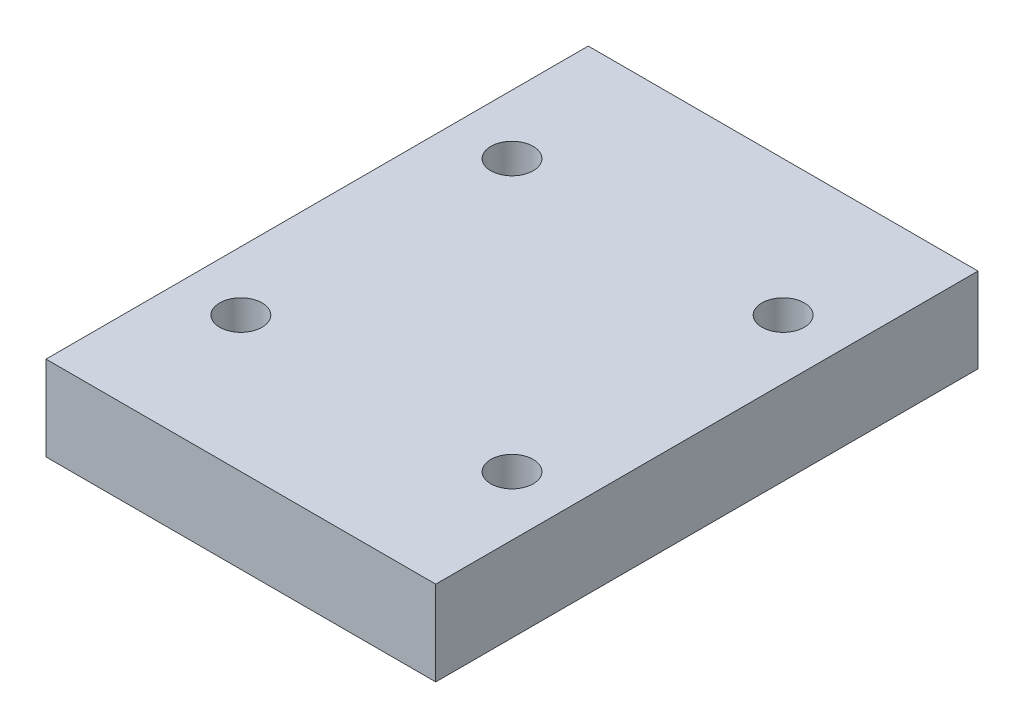
SolidWorks part; units mm, degrees
ref_plane "前视基准面" through (0, 0, 0) normal (0, 0, 1) x (1, 0, 0)
ref_plane "上视基准面" through (0, 0, 0) normal (0, 1, 0) x (1, 0, 0)
ref_plane "右视基准面" through (0, 0, 0) normal (1, 0, 0) x (0, 0, -1)
sketch "草图1" plane through (0, 0, 0) normal (0, 1, 0) x (1, 0, 0)
  line L1 (11.5, 16) -> (-11.5, 16)
  line L2 (11.5, 16) -> (11.5, -16)
  line L3 (11.5, -16) -> (-11.5, -16)
  line L4 (-11.5, 16) -> (-11.5, -16)
  line L5 (11.5, 16) -> (-11.5, -16) construction
  line L6 (11.5, -16) -> (-11.5, 16) construction
  circle A0 centre (-8, -8) radius 1.25
  circle A1 centre (-8, 8) radius 1.25
  circle A2 centre (8, 8) radius 1.25
  circle A3 centre (8, -8) radius 1.25
  point P0 (0, 0)
  dimension "D5" = 16
  dimension "D1" = 3.5
  dimension "D3" = 32
  dimension "D4" = 23
extrude "凸台-拉伸1" add sketch "草图1" along normal blind 5
